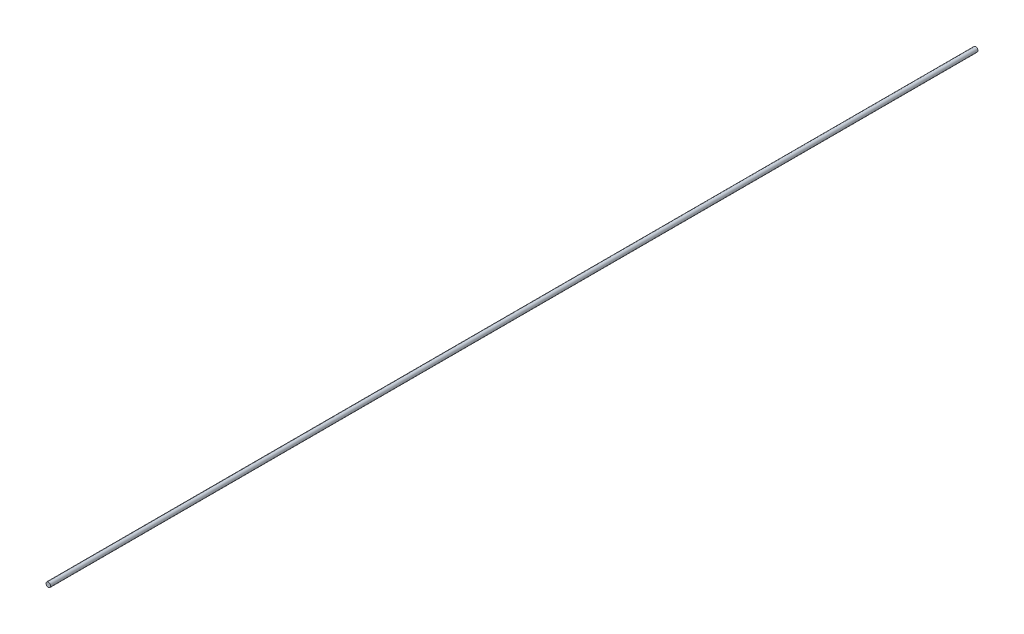
SolidWorks part; units mm, degrees
material "Настроенная пользователем пластмасса"
ref_plane "Front" through (0, 0, 0) normal (0, 0, 1) x (1, 0, 0)
ref_plane "Top" through (0, 0, 0) normal (0, 1, 0) x (1, 0, 0)
ref_plane "Right" through (0, 0, 0) normal (1, 0, 0) x (0, 0, -1)
sketch "Эскиз1" plane through (0, 0, 0) normal (0, 0, 1) x (1, 0, 0)
  circle A0 centre (0, 0) radius 0.5
extrude "Бобышка-Вытянуть1" add sketch "Эскиз1" along normal blind 200
